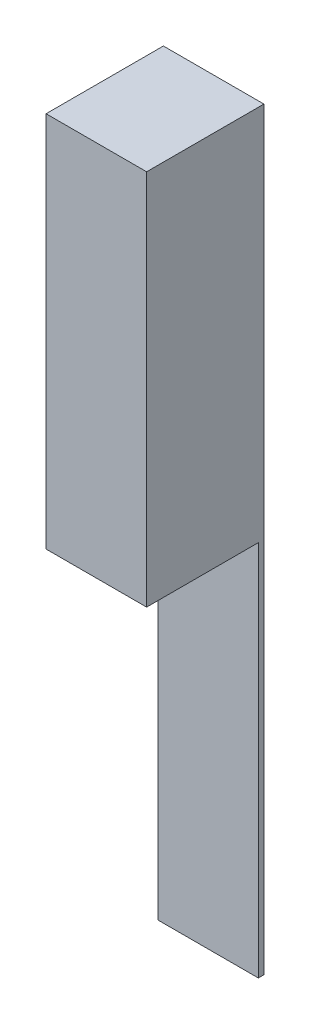
SolidWorks part; units mm, degrees
ref_plane "前视基准面" through (0, 0, 0) normal (0, 0, 1) x (1, 0, 0)
ref_plane "上视基准面" through (0, 0, 0) normal (0, 1, 0) x (1, 0, 0)
ref_plane "右视基准面" through (0, 0, 0) normal (1, 0, 0) x (0, 0, -1)
sketch "草图1" plane through (0, 0, 0) normal (0, 0, 1) x (1, 0, 0)
  line L1 (-13.0225, 22.0421) -> (166.9775, 22.0421)
  line L2 (-13.0225, 22.0421) -> (-13.0225, -1327.9579)
  line L3 (-13.0225, -1327.9579) -> (166.9775, -1327.9579)
  line L4 (166.9775, 22.0421) -> (166.9775, -1327.9579)
extrude "凸台-拉伸1" add sketch "草图1" along normal blind 10
sketch "草图2" plane through (0, 0, 10) normal (0, 0, 1) x (1, 0, 0)
  line L0 (166.9775, -1327.9579) -> (166.9775, 22.0421) construction
  line L1 (-13.0225, 22.0421) -> (166.9775, 22.0421)
  line L2 (-13.0225, 22.0421) -> (-13.0225, -652.9579)
  line L3 (-13.0225, -652.9579) -> (166.9775, -652.9579)
  line L4 (166.9775, 22.0421) -> (166.9775, -652.9579)
extrude "凸台-拉伸2" add sketch "草图2" along normal blind 200
scale "缩放比例1" scale about origin uniform scaling yes scale factor 0.345
